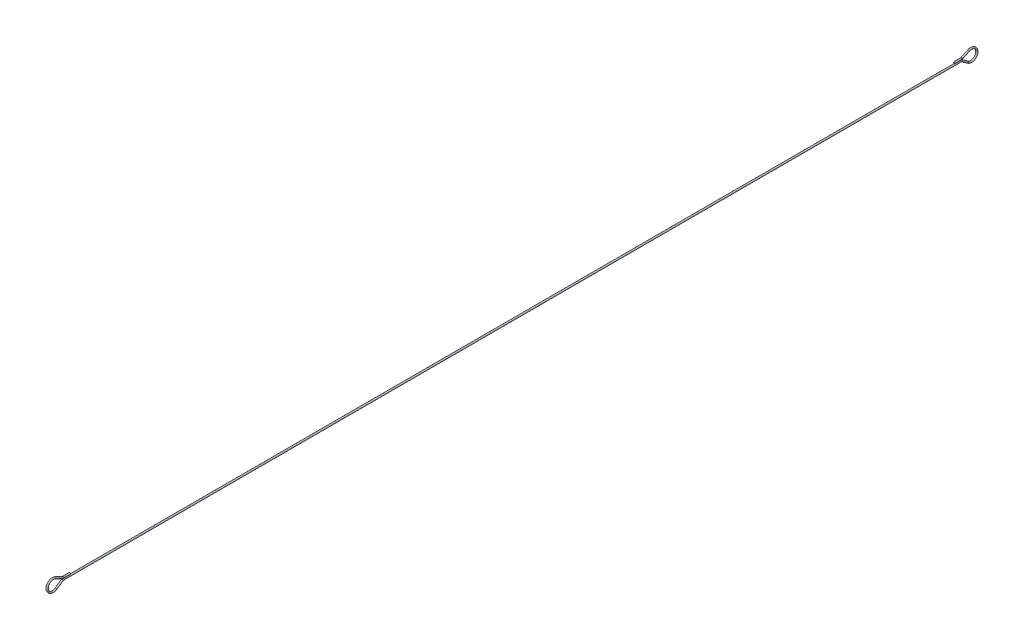
SolidWorks part; units mm, degrees
material "Plain Carbon Steel"
ref_plane "Front Plane" through (0, 0, 0) normal (0, 0, 1) x (1, 0, 0)
ref_plane "Top Plane" through (0, 0, 0) normal (0, 1, 0) x (1, 0, 0)
ref_plane "Right Plane" through (0, 0, 0) normal (1, 0, 0) x (0, 0, -1)
sketch "Sketch1" plane through (0, 0, 0) normal (1, 0, 0) x (0, 0, -1)
  line L0 (0, 0) -> (-882.6891, 0)
  line L1 (-884.5008, -0.5676) -> (-896.8896, -9.1759)
  line L2 (-898.5068, 10.1096) -> (-884.8574, 3.6848)
  line L3 (-882.6891, 3.2) -> (-869.9891, 3.2)
  line L4 (-882.6891, 3.2) -> (-882.6891, 0) construction
  line L5 (55, 0) -> (-55, 0) construction
  arc A0 (-882.6891, 0) -> (-884.5008, -0.5676) centre (-882.6891, -3.175) ccw
  arc A1 (-896.8896, -9.1759) -> (-898.5068, 10.1096) centre (-903.2655, 0) cw
  arc A2 (-884.8574, 3.6848) -> (-882.6891, 3.2) centre (-882.6891, 8.2913) ccw
  point P16 (-914.4, -0.9337)
  dimension "D3" = 3.175
  dimension "D1" = 3.2
  dimension "D2" = 12.7
  dimension "D4" = 31.75
  dimension "D5" = 60
  dimension "D6" = 914.4
sketch "Sketch2" plane through (0, 0, 0) normal (0, 0, 1) x (1, 0, 0)
  line L0 (0, -11.1736) -> (0, 11.1736) construction
  circle A0 centre (0, 0) radius 1.5875
  dimension "D1" = 3.175
sweep "Sweep1" add profiles "Sketch2" path "Sketch1"
mirror "Mirror1" about plane through (0, 0, 0) normal (0, 0, 1) of "Sweep1"
